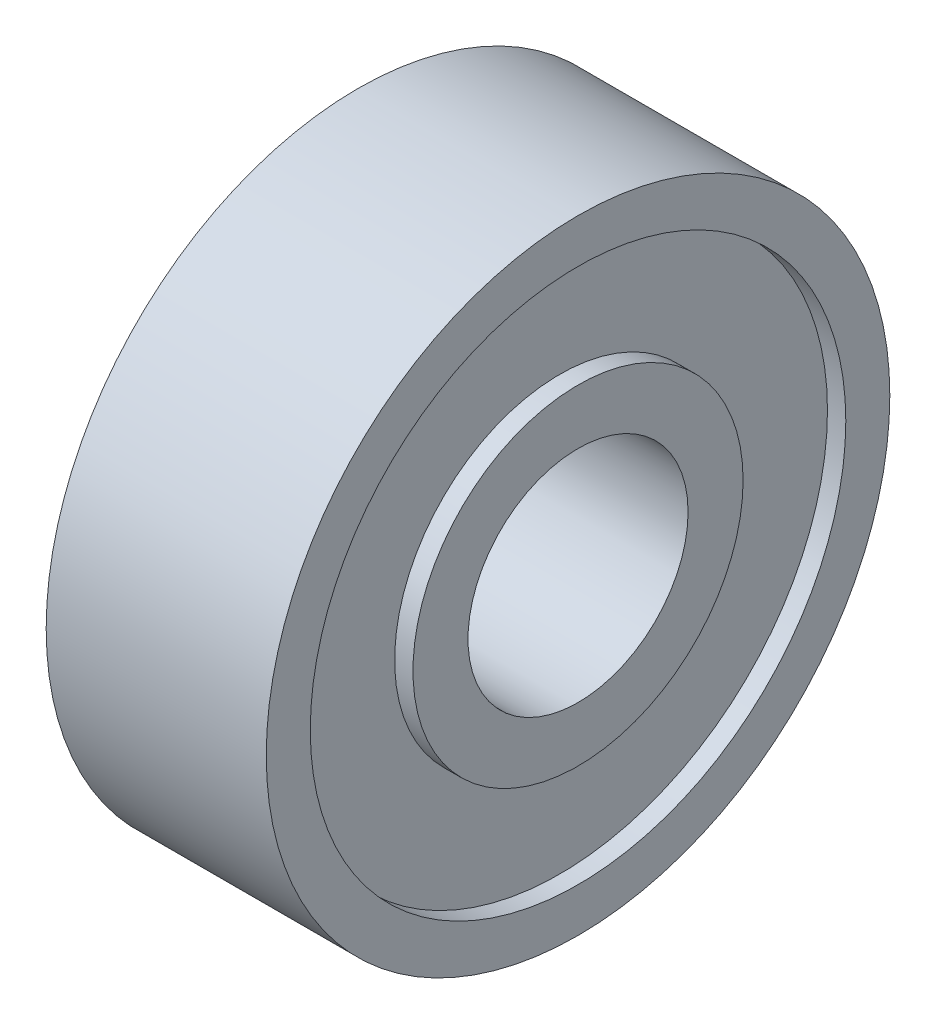
SolidWorks part; units mm, degrees
ref_plane "Alzado" through (0, 0, 0) normal (0, 0, 1) x (1, 0, 0)
ref_plane "Planta" through (0, 0, 0) normal (0, 1, 0) x (1, 0, 0)
ref_plane "Vista lateral" through (0, 0, 0) normal (1, 0, 0) x (0, 0, -1)
sketch "Croquis2" plane through (0, 0, 0) normal (0, 0, 1) x (1, 0, 0)
  line L0 (3, 8.5) -> (-3, 8.5)
  line L1 (-3, 8.5) -> (-3, 7.3)
  line L2 (-3, 7.3) -> (-2.5, 7.3)
  line L3 (-2.5, 7.3) -> (-2.5, 4.5)
  line L4 (-2.5, 4.5) -> (-3, 4.5)
  line L5 (-3, 4.5) -> (-3, 3)
  line L6 (-3, 3) -> (3, 3)
  line L7 (0, 3) -> (0, 8.5)
  line L8 (6.7719, 0) -> (-8.2965, 0) construction
  line L9 (0, 0) -> (0, 22.1902) construction
  line L10 (3, 4.5) -> (3, 3)
  line L11 (2.5, 4.5) -> (3, 4.5)
  line L12 (2.5, 7.3) -> (2.5, 4.5)
  line L13 (3, 7.3) -> (2.5, 7.3)
  line L14 (3, 8.5) -> (3, 7.3)
  dimension "D1" = 3
  dimension "D2" = 8.5
  dimension "D3" = 1.2
  dimension "D4" = 1.5
  dimension "D5" = 0.5
  dimension "D6" = 3
revolve "Revolución1" add sketch "Croquis2" angle 360 about L8
